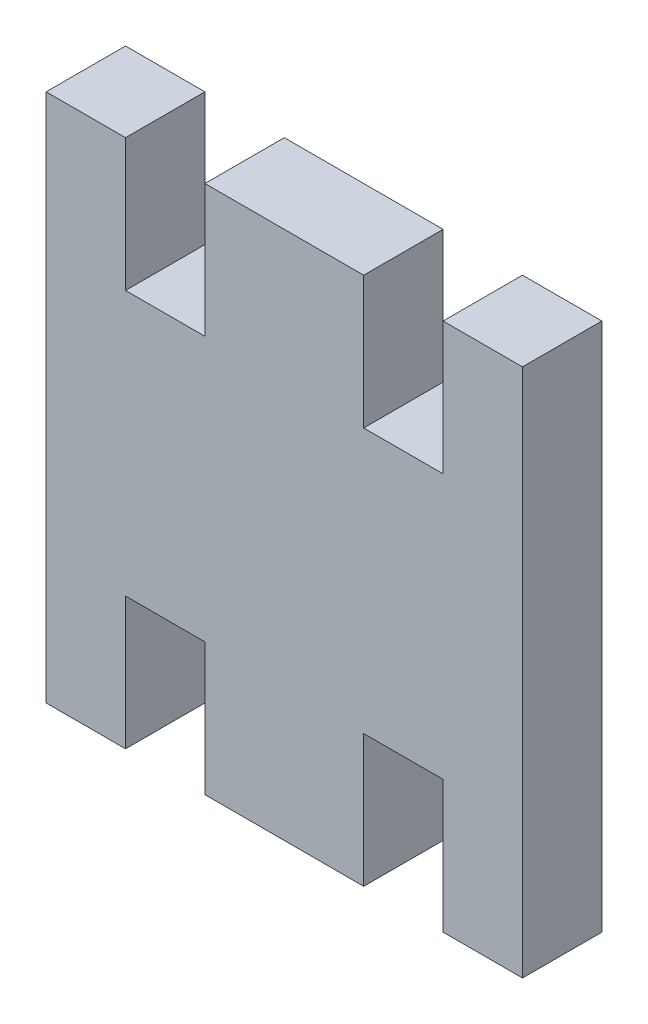
SolidWorks part; units mm, degrees
ref_plane "Front" through (0, 0, 0) normal (0, 0, 1) x (1, 0, 0)
ref_plane "Top" through (0, 0, 0) normal (0, 1, 0) x (1, 0, 0)
ref_plane "Right" through (0, 0, 0) normal (1, 0, 0) x (0, 0, -1)
sketch "Sketch1" plane through (0, 0, 0) normal (0, 0, 1) x (1, 0, 0)
  line L1 (0, 0) -> (-36, 0)
  line L2 (0, 0) -> (0, 40)
  line L3 (0, 40) -> (-36, 40)
  line L4 (-36, 0) -> (-36, 40)
  dimension "D1" = 36
  dimension "D2" = 40
extrude "Boss-Extrude1" add sketch "Sketch1" along normal blind 6
sketch "Sketch2" plane through (0, 0, 6) normal (0, 0, 1) x (1, 0, 0)
  line L0 (0, 40) -> (-36, 40) construction
  line L1 (-30, 40) -> (-24, 40)
  line L2 (-30, 40) -> (-30, 30)
  line L3 (-30, 30) -> (-24, 30)
  line L4 (-24, 40) -> (-24, 30)
  line L5 (-36, 40) -> (-36, 0) construction
  dimension "D1" = 6
  dimension "D2" = 6
  dimension "D3" = 10
extrude "Cut-Extrude1" cut sketch "Sketch2" against normal through all
pattern_linear "LPattern1" count 2 spacing 18 along (1, 0, 0) count 2 spacing 30 along (0, -1, 0) of "Cut-Extrude1"
